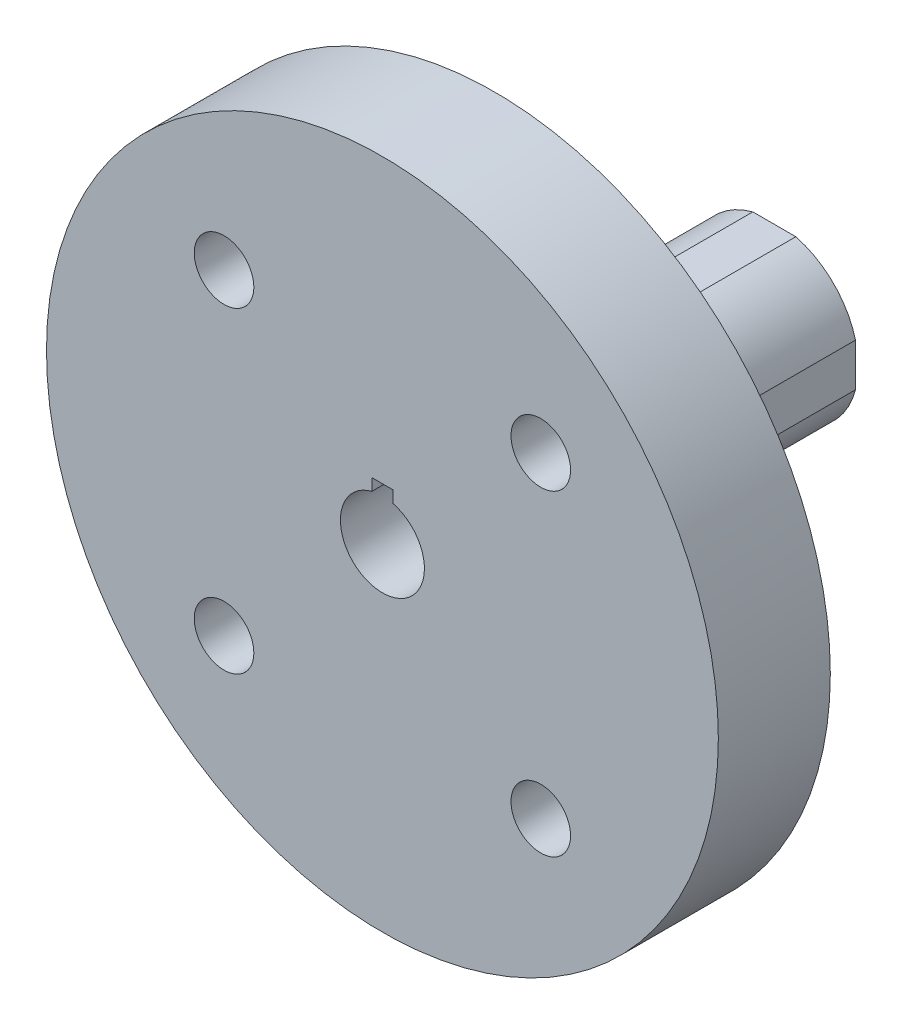
SolidWorks part; units mm, degrees
ref_plane "Front Plane" through (0, 0, 0) normal (0, 0, 1) x (1, 0, 0)
ref_plane "Top Plane" through (0, 0, 0) normal (0, 1, 0) x (1, 0, 0)
ref_plane "Right Plane" through (0, 0, 0) normal (1, 0, 0) x (0, 0, -1)
sketch "Sketch1" plane through (0, 0, 0) normal (0, 0, 1) x (1, 0, 0)
  circle A0 centre (0, 0) radius 76.2
  dimension "D1" = 152.4
extrude "Boss-Extrude1" add sketch "Sketch1" along normal blind 25.4
sketch "Sketch2" plane through (0, 0, 0) normal (0, 0, -1) x (-1, 0, 0)
  circle A0 centre (0, 0) radius 19.05
  dimension "D1" = 38.1
extrude "Boss-Extrude2" add sketch "Sketch2" along normal blind 63.5
sketch "Sketch4" plane through (0, 0, -63.5) normal (0, 0, -1) x (-1, 0, 0)
  line L0 (-4.8775, 18.415) -> (4.8775, 18.415)
  line L1 (-18.415, 4.8775) -> (-18.415, -4.8775)
  line L2 (4.8775, -18.415) -> (-4.8775, -18.415)
  line L3 (18.415, 4.8775) -> (18.415, -4.8775)
  arc A0 (4.8775, 18.415) -> (-4.8775, 18.415) centre (0, 0) ccw
  circle A1 centre (0, 0) radius 19.05 construction
  circle A2 centre (0, 0) radius 19.05 construction
  arc A3 (18.415, 4.8775) -> (18.415, -4.8775) centre (0, 0) cw
  arc A4 (-4.8775, -18.415) -> (4.8775, -18.415) centre (0, 0) ccw
  arc A5 (-18.415, 4.8775) -> (-18.415, -4.8775) centre (0, 0) ccw
  dimension "D1" = 18.415
  dimension "D2" = 18.415
  dimension "D3" = 18.415
  dimension "D4" = 18.415
extrude "Cut-Extrude1" cut sketch "Sketch4" against normal blind 63.5
sketch "Sketch6" plane through (0, 0, 0) normal (0, 0, -1) x (-1, 0, 0)
  line L0 (-4.8775, 18.415) -> (-4.8775, 50.165)
  line L1 (4.8775, 18.415) -> (-4.8775, 18.415)
  line L2 (4.8775, 18.415) -> (4.8775, 50.165)
  line L3 (4.8775, 50.165) -> (-4.8775, 50.165)
  dimension "D1" = 31.75
extrude "Boss-Extrude7" add sketch "Sketch6" along normal blind 31.75
sketch "Sketch7" plane through (4.8775, 0, 0) normal (1, 0, 0) x (0, 0, -1)
  line L1 (31.75, 18.415) -> (0, 50.165)
  line L2 (0, 50.165) -> (31.75, 50.165)
  line L3 (31.75, 50.165) -> (31.75, 18.415)
extrude "Cut-Extrude2" cut sketch "Sketch7" against normal blind 31.75
sketch "Sketch8" plane through (0, 0, 25.4) normal (0, 0, 1) x (1, 0, 0)
  circle A0 centre (0, 0) radius 9.525
  dimension "D1" = 19.05
extrude "Cut-Extrude3" cut sketch "Sketch8" against normal through all
sketch "Sketch9" plane through (0, 0, 25.4) normal (0, 0, 1) x (1, 0, 0)
  line L1 (-2.3813, 11.9062) -> (-2.3813, 9.2225)
  line L2 (-2.3813, 11.9062) -> (2.3813, 11.9062)
  line L3 (2.3813, 11.9062) -> (2.3813, 9.2225)
  circle A1 centre (0, 0) radius 9.525 construction
  arc A2 (2.3813, 9.2225) -> (-2.3813, 9.2225) centre (0, 0) ccw
  point P3 (0, 9.525)
  dimension "D3" = 2.3813
extrude "Cut-Extrude4" cut sketch "Sketch9" against normal through all
sketch "Sketch11" plane through (0, 0, 0) normal (0, 0, -1) x (-1, 0, 0)
  line L0 (4.8775, -18.415) -> (-4.8775, -18.415)
  line L1 (-4.8775, -18.415) -> (-4.8775, -50.165)
  line L2 (-4.8775, -50.165) -> (4.8775, -50.165)
  line L3 (4.8775, -50.165) -> (4.8775, -18.415)
  dimension "D1" = 31.75
extrude "Boss-Extrude8" add sketch "Sketch11" along normal blind 31.75
sketch "Sketch12" plane through (-4.8775, 0, 0) normal (-1, 0, 0) x (0, 0, 1)
  line L0 (-31.75, -18.415) -> (0, -50.165)
  line L1 (0, -50.165) -> (-31.75, -50.165)
  line L2 (-31.75, -50.165) -> (-31.75, -18.415)
extrude "Cut-Extrude5" cut sketch "Sketch12" against normal through all
sketch "Sketch13" plane through (0, 0, 0) normal (0, 0, -1) x (-1, 0, 0)
  line L0 (18.415, -4.8775) -> (18.415, 4.8775)
  line L2 (18.415, 4.8775) -> (50.165, 4.8775)
  line L3 (50.165, 4.8775) -> (50.165, -4.8775)
  line L4 (50.165, -4.8775) -> (18.415, -4.8775)
  dimension "D1" = 31.75
extrude "Boss-Extrude9" add sketch "Sketch13" along normal blind 31.75
sketch "Sketch14" plane through (0, 4.8775, 0) normal (0, 1, 0) x (1, 0, 0)
  line L0 (-18.415, 31.75) -> (-50.165, 0)
  line L1 (-50.165, 0) -> (-50.165, 31.75)
  line L2 (-50.165, 31.75) -> (-18.415, 31.75)
extrude "Cut-Extrude6" cut sketch "Sketch14" against normal through all
sketch "Sketch15" plane through (0, 0, 0) normal (0, 0, -1) x (-1, 0, 0)
  line L0 (-18.415, -4.8775) -> (-18.415, 4.8775)
  line L1 (-18.415, 4.8775) -> (-50.165, 4.8775)
  line L2 (-50.165, 4.8775) -> (-50.165, -4.8775)
  line L3 (-50.165, -4.8775) -> (-18.415, -4.8775)
  dimension "D1" = 31.75
extrude "Boss-Extrude10" add sketch "Sketch15" along normal blind 31.75
sketch "Sketch16" plane through (0, -4.8775, 0) normal (0, -1, 0) x (1, 0, 0)
  line L0 (18.415, -31.75) -> (50.165, 0)
  line L1 (50.165, 0) -> (50.165, -31.75)
  line L2 (50.165, -31.75) -> (18.415, -31.75)
extrude "Cut-Extrude7" cut sketch "Sketch16" against normal through all
sketch "Sketch17" plane through (0, 0, 25.4) normal (0, 0, 1) x (1, 0, 0)
  circle A5 centre (35.921, 35.921) radius 6.7564
  circle A6 centre (-35.921, -35.921) radius 6.7564
  circle A7 centre (-35.921, 35.921) radius 6.7564
  circle A8 centre (35.921, -35.921) radius 6.7564
  dimension "D1" = 13.5128
  dimension "D4" = 13.5128
  dimension "D5" = 13.5128
  dimension "D6" = 13.5128
extrude "Cut-Extrude8" cut sketch "Sketch17" against normal through all
